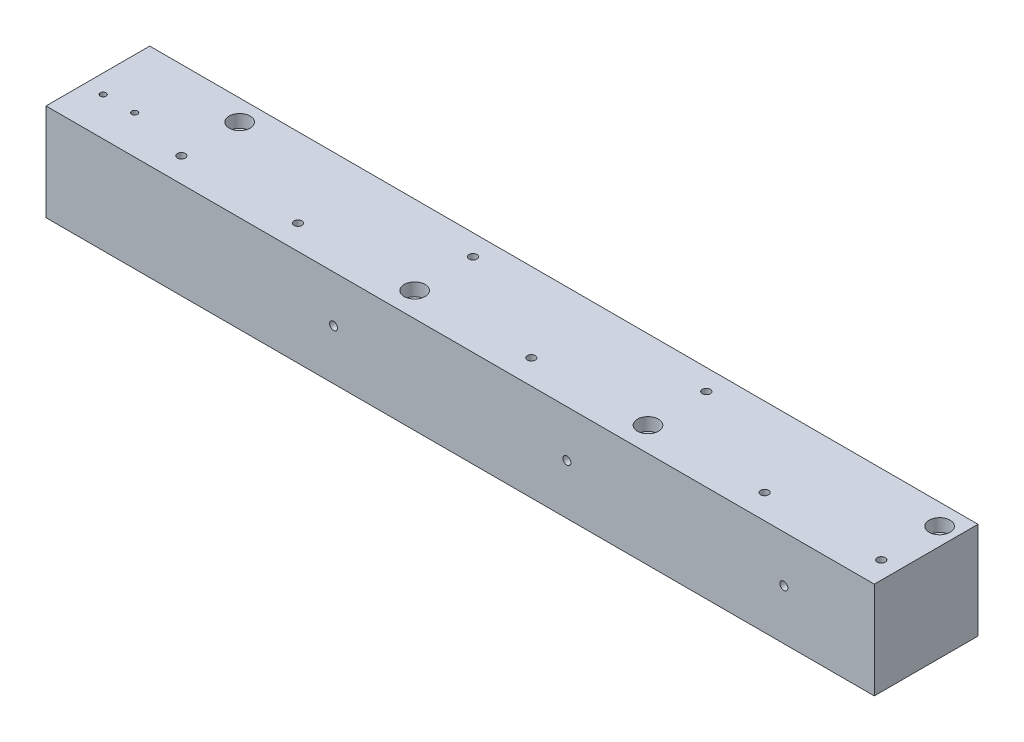
SolidWorks part; units mm, degrees
material "Low Carbon Steel"
ref_plane "Front Plane" through (0, 0, 0) normal (0, 0, 1) x (1, 0, 0)
ref_plane "Top Plane" through (0, 0, 0) normal (0, 1, 0) x (1, 0, 0)
ref_plane "Right Plane" through (0, 0, 0) normal (1, 0, 0) x (0, 0, -1)
sketch "Sketch1" plane through (0, 0, 0) normal (0, 0, 1) x (1, 0, 0)
  line L1 (0, 0) -> (710, 0)
  line L2 (0, 0) -> (0, 83)
  line L3 (0, 83) -> (710, 83)
  line L4 (710, 0) -> (710, 83)
  dimension "D1" = 83
  dimension "D2" = 710
extrude "Boss-Extrude1" add sketch "Sketch1" along normal blind 88.9
hole_wizard "M8 Tapped Hole1" positions "Sketch6" profile "Sketch5" tap size "M8" standard "Peddi DIN"
sketch "Sketch6" plane through (0, 83, 0) normal (0, 1, 0) x (1, 0, 0)
  line L9 (710, -88.9) -> (0, -88.9) construction
  line L10 (95, -67.9) -> (195, -67.9) construction
  line L11 (195, -67.9) -> (395, -67.9) construction
  line L12 (395, -67.9) -> (595, -67.9) construction
  line L13 (595, -67.9) -> (695, -67.9) construction
  line L15 (495, -17.9) -> (495, -67.9) construction
  line L17 (295, -17.9) -> (295, -67.9) construction
  line L19 (395, -67.9) -> (395, 0) construction
  line L21 (710, 0) -> (0, 0) construction
  line L23 (710, -88.9) -> (710, 0) construction
  point P2 (95, -67.9)
  point P4 (195, -67.9)
  point P8 (295, -17.9)
  point P14 (395, -67.9)
  point P22 (495, -17.9)
  point P24 (595, -67.9)
  point P26 (695, -67.9)
  dimension "D2" = 21
  dimension "D3" = 100
  dimension "D4" = 50
  dimension "D5" = 315
  dimension "D10" = 200
sketch "Sketch5" plane through (95, 83, 67.9) normal (1, 0, 0) x (0, 0, 1)
  line L0 (0, 0) -> (0, 35.0329)
  line L1 (0, 35.0329) -> (3.4, 32.99)
  line L2 (3.4, 32.99) -> (3.4, 0)
  line L5 (3.4, 0) -> (0, 0)
  line L10 (0, 35.0329) -> (-3.4, 32.99) construction
  line L11 (0, -6.35) -> (0, 107.95) construction
  dimension "Tap Drill Dia." = 6.8
  dimension "Tap Drill Depth" = 32.99
  dimension "Drill Angle" = 118
cosmetic thread "Hole Thread7" parameters "D1"=19.99, "D2"=8
cosmetic thread "Hole Thread8" parameters "D1"=19.99, "D2"=8
cosmetic thread "Hole Thread9" parameters "D1"=19.99, "D2"=8
cosmetic thread "Hole Thread13" parameters "D1"=19.99, "D2"=8
cosmetic thread "Hole Thread16" parameters "D1"=19.99, "D2"=8
cosmetic thread "Hole Thread18" parameters "D1"=19.99, "D2"=8
cosmetic thread "Hole Thread19" parameters "D1"=19.99, "D2"=8
hole_wizard "CBORE for M10 Hex Socket Head Cap Screw1" positions "Sketch8" profile "Sketch7" counterbore size "M10" standard "Peddi DIN" end condition through all
sketch "Sketch8" plane through (0, 83, 0) normal (0, 1, 0) x (1, 0, 0)
  line L14 (95, -67.9) -> (95, -17.9) construction
  line L17 (695, -67.9) -> (695, -17.9) construction
  line L33 (95, -17.9) -> (295, -17.9) construction
  line L35 (295, -67.9) -> (295, -17.9) construction
  line L37 (295, -67.9) -> (395, -67.9) construction
  line L38 (395, -67.9) -> (495, -67.9) construction
  line L39 (495, -67.9) -> (495, -17.9) construction
  line L40 (495, -17.9) -> (695, -17.9) construction
  point P0 (695, -17.9)
  point P2 (495, -67.9)
  point P4 (295, -67.9)
  point P6 (95, -17.9)
sketch "Sketch7" plane through (695, 83, 17.9) normal (1, 0, 0) x (0, 0, 1)
  line L0 (0, 0) -> (0, 83)
  line L1 (0, 83) -> (5.5, 83)
  line L3 (5.5, 83) -> (5.5, 11)
  line L4 (5.5, 11) -> (9, 11)
  line L5 (9, 11) -> (9, 0)
  line L7 (9, 0) -> (0, 0)
  line L11 (0, -6.35) -> (0, 107.95) construction
  dimension "Thru Hole Dia." = 11
  dimension "Thru Hole Depth" = 83
  dimension "C'Bore Dia." = 18
  dimension "C'Bore Depth" = 11
hole_wizard "M6 Tapped Hole1" positions "Sketch10" profile "Sketch9" tap size "M6" standard "Peddi DIN"
sketch "Sketch10" plane through (0, 83, 0) normal (0, 1, 0) x (1, 0, 0)
  line L0 (16, -55.9) -> (43, -55.9) construction
  line L2 (95, -55.9) -> (43, -55.9) construction
  line L3 (95, -55.9) -> (95, -67.9) construction
  point P0 (16, -55.9)
  point P2 (43, -55.9)
  dimension "D1" = 27
  dimension "D2" = 52
  dimension "D3" = 12
sketch "Sketch9" plane through (16, 83, 55.9) normal (1, 0, 0) x (0, 0, 1)
  line L0 (0, 0) -> (0, 22.8522)
  line L1 (0, 22.8522) -> (2.5, 21.35)
  line L2 (2.5, 21.35) -> (2.5, 0)
  line L5 (2.5, 0) -> (0, 0)
  line L10 (0, 22.8522) -> (-2.5, 21.35) construction
  line L11 (0, -6.35) -> (0, 107.95) construction
  dimension "Tap Drill Dia." = 5
  dimension "Tap Drill Depth" = 21.35
  dimension "Drill Angle" = 118
cosmetic thread "Hole Thread20" parameters "D1"=15, "D2"=6
cosmetic thread "Hole Thread21" parameters "D1"=15, "D2"=6
hole_wizard "M8 Tapped Hole2" positions "Sketch11" profile "Sketch12" tap size "M8" standard "Peddi DIN"
sketch "Sketch11" plane through (0, 0, 88.9) normal (0, 0, 1) x (1, 0, 0)
  line L0 (246.5, 43) -> (446.5, 43) construction
  line L1 (446.5, 43) -> (632.5, 43) construction
  line L4 (710, 0) -> (710, 83) construction
  line L5 (0, 0) -> (710, 0) construction
  point P0 (246.5, 43)
  point P2 (446.5, 43)
  point P4 (632.5, 43)
  dimension "D1" = 43
  dimension "D2" = 77.5
  dimension "D3" = 186
  dimension "D4" = 386
sketch "Sketch12" plane through (246.5, 43, 88.9) normal (1, 0, 0) x (0, -1, 0)
  line L0 (0, 0) -> (0, 35.0329)
  line L1 (0, 35.0329) -> (3.4, 32.99)
  line L2 (3.4, 32.99) -> (3.4, 0)
  line L5 (3.4, 0) -> (0, 0)
  line L10 (0, 35.0329) -> (-3.4, 32.99) construction
  line L11 (0, -6.35) -> (0, 107.95) construction
  dimension "Tap Drill Dia." = 6.8
  dimension "Tap Drill Depth" = 32.99
  dimension "Drill Angle" = 118
cosmetic thread "Hole Thread22" parameters "D1"=19.99, "D2"=8
cosmetic thread "Hole Thread23" parameters "D1"=19.99, "D2"=8
cosmetic thread "Hole Thread24" parameters "D1"=19.99, "D2"=8
other "Freeze***"
